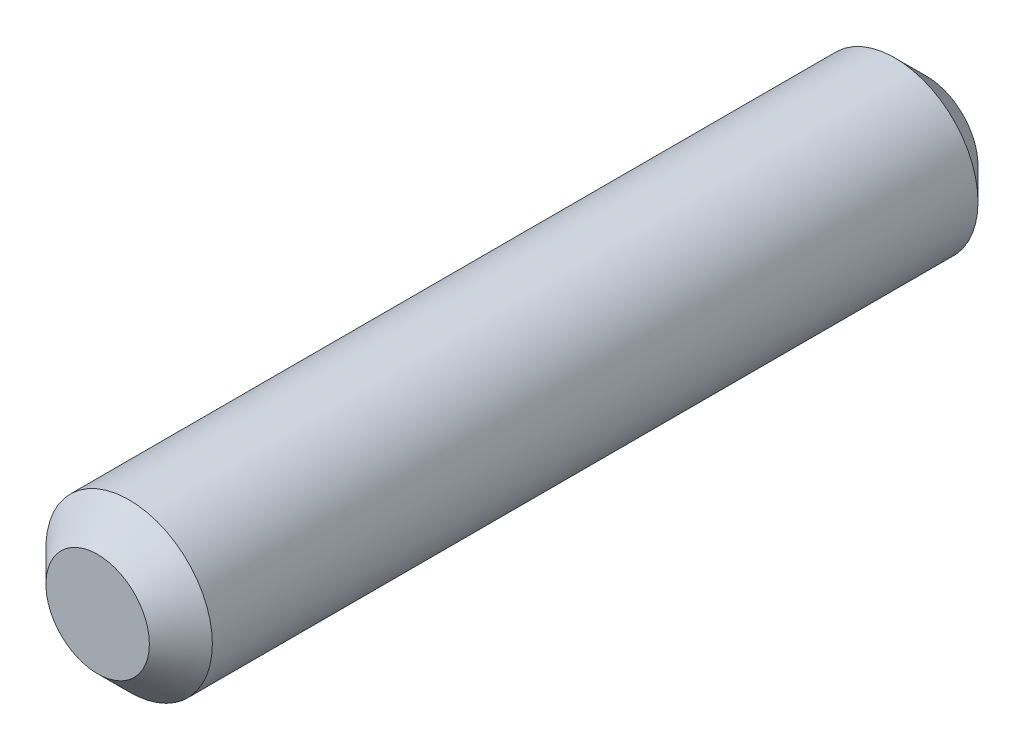
SolidWorks part; units mm, degrees
ref_plane "Front Plane" through (0, 0, 0) normal (0, 0, 1) x (1, 0, 0)
ref_plane "Top Plane" through (0, 0, 0) normal (0, 1, 0) x (1, 0, 0)
ref_plane "Right Plane" through (0, 0, 0) normal (1, 0, 0) x (0, 0, -1)
sketch "Sketch1" plane through (0, 0, 0) normal (0, 0, 1) x (1, 0, 0)
  circle A0 centre (0, 0) radius 1.585
  dimension "D1" = 3.17
extrude "Boss-Extrude1" add sketch "Sketch1" along normal mid plane 15.78
chamfer "Chamfer1" distance 0.6 angle 45 2 edges at (1.585, 0, 7.89) (1.585, 0, -7.89)
